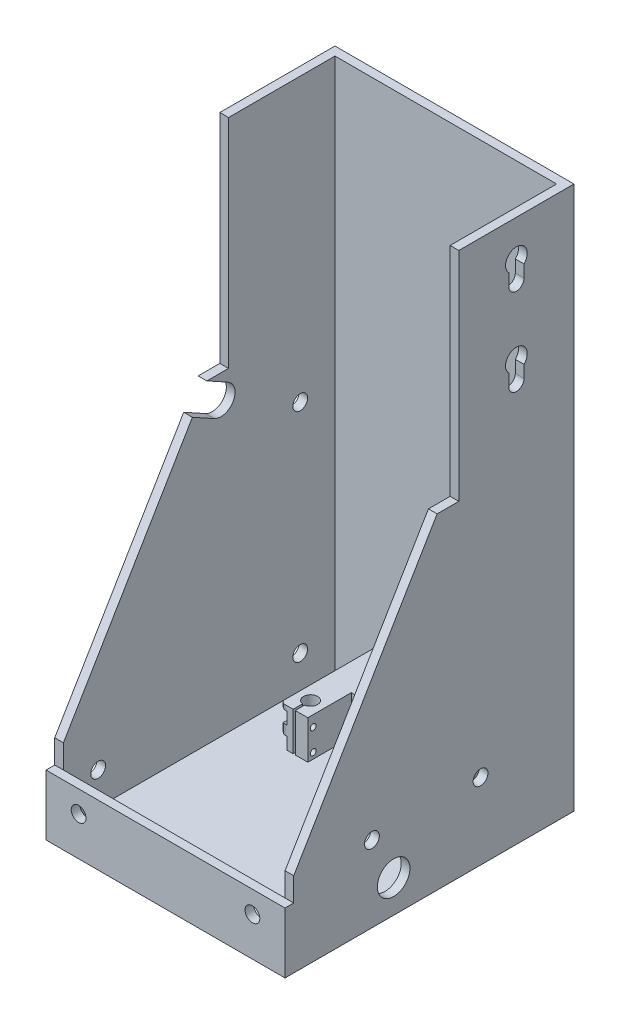
SolidWorks part; units mm, degrees
ref_plane "Front Plane" through (0, 0, 0) normal (0, 0, 1) x (1, 0, 0)
ref_plane "Top Plane" through (0, 0, 0) normal (0, 1, 0) x (1, 0, 0)
ref_plane "Right Plane" through (0, 0, 0) normal (1, 0, 0) x (0, 0, -1)
sketch "Sketch3" plane through (0, 0, 0) normal (0, 1, 0) x (1, 0, 0)
  line L0 (-55, 66.5) -> (55, 66.5)
  line L1 (55, 66.5) -> (55, -66.5)
  line L2 (55, -66.5) -> (-55, -66.5)
  line L3 (-55, -66.5) -> (-55, 66.5)
  point P2 (0, 66.5)
  point P6 (-55, 0)
  dimension "D1" = 133
  dimension "D2" = 110
extrude "Boss-Extrude1" add sketch "Sketch3" along normal blind 5
sketch "Sketch4" plane through (0, 5, 0) normal (0, 1, 0) x (1, 0, 0)
  line L0 (-55, -66.5) -> (-55, 66.5)
  line L1 (-55, 66.5) -> (55, 66.5)
  line L2 (55, 66.5) -> (55, -66.5)
  line L3 (55, -66.5) -> (-55, -66.5)
  line L4 (-51, 62.5) -> (51, 62.5)
  line L5 (51, 62.5) -> (51, -62.5)
  line L6 (51, -62.5) -> (-51, -62.5)
  line L7 (-51, -62.5) -> (-51, 62.5)
  dimension "D1" = 4
  dimension "D2" = 4
  dimension "D3" = 4
  dimension "D4" = 4
extrude "Boss-Extrude2" add sketch "Sketch4" along normal blind 245
sketch "Sketch5" plane through (-55, 0, 0) normal (-1, 0, 0) x (0, 0, 1)
  line L0 (-13.5, 250) -> (-13.5, 150)
  line L1 (-66.5, 250) -> (66.5, 250) construction
  line L2 (-13.5, 150) -> (-3.5, 150)
  line L3 (66.5, 27.9) -> (62.5, 27.9)
  line L4 (66.5, 250) -> (66.5, 0) construction
  line L5 (62.5, 27.9) -> (62.5, 38.76)
  line L6 (-3.5, 150) -> (62.5, 38.76)
  line L7 (-13.5, 250) -> (66.5, 250)
  line L8 (66.5, 250) -> (66.5, 27.9)
  dimension "D1" = 100
  dimension "D2" = 53
  dimension "D3" = 10
  dimension "D4" = 27.9
  dimension "D5" = 4
  dimension "D6" = 10.86
extrude "Cut-Extrude1" cut sketch "Sketch5" against normal through all
sketch "Sketch6" plane through (0, 5, 0) normal (0, 1, 0) x (1, 0, 0)
  line L0 (-31, 62.5) -> (31.5, 62.5)
  line L1 (51, 62.5) -> (-51, 62.5) construction
  line L2 (-31, 62.5) -> (-31, 37.5)
  line L3 (-31, 37.5) -> (31.5, 37.5)
  line L4 (31.5, 37.5) -> (31.5, 62.5)
  dimension "D1" = 20
  dimension "D2" = 19.5
  dimension "D3" = 25
extrude "Boss-Extrude3" add sketch "Sketch6" along normal blind 20
sketch "Sketch7" plane through (0, 25, 0) normal (0, 1, 0) x (1, 0, 0)
  line L0 (31.5, 62.5) -> (-31, 62.5) construction
  line L1 (31.5, 37.5) -> (31.5, 62.5) construction
  circle A0 centre (0.25, 45) radius 2.75
  dimension "D1" = 5.5
  dimension "D2" = 17.5
  dimension "D3" = 31.25
extrude "Cut-Extrude2" cut sketch "Sketch7" against normal blind 20
sketch "Sketch8" plane through (0, 5, 0) normal (0, 1, 0) x (1, 0, 0)
  line L0 (-31, 37.5) -> (-31, 17.5)
  line L1 (-31, 17.5) -> (-18.5, 17.5)
  line L2 (-18.5, 17.5) -> (-18.5, 37.5)
  line L3 (-31, 37.5) -> (31.5, 37.5) construction
  line L4 (-18.5, 37.5) -> (-31, 37.5)
  line L5 (31.5, 37.5) -> (31.5, 17.5)
  line L6 (31.5, 17.5) -> (19, 17.5)
  line L7 (19, 17.5) -> (19, 37.5)
  line L8 (-31, 37.5) -> (31.5, 37.5) construction
  line L9 (19, 37.5) -> (31.5, 37.5)
  dimension "D1" = 20
  dimension "D2" = 20
  dimension "D3" = 12.5
  dimension "D4" = 12.5
extrude "Boss-Extrude4" add sketch "Sketch8" along normal blind 20
sketch "Sketch9" plane through (0, 25, 0) normal (0, 1, 0) x (1, 0, 0)
  line L0 (-18.5, 37.5) -> (19, 37.5) construction
  line L1 (19, 37.5) -> (19, 17.5) construction
  line L2 (-18.5, 17.5) -> (-18.5, 37.5) construction
  circle A0 centre (-24.75, 25) radius 3.25
  circle A1 centre (25.25, 25) radius 3.25
  dimension "D1" = 6.5
  dimension "D2" = 6.5
  dimension "D3" = 12.5
  dimension "D4" = 6.25
  dimension "D5" = 6.25
extrude "Cut-Extrude3" cut sketch "Sketch9" against normal blind 20
sketch "Sketch10" plane through (-18.5, 0, 0) normal (1, 0, 0) x (0, 0, -1)
  line L0 (37.5, 5) -> (37.5, 7.25)
  line L1 (37.5, 25) -> (37.5, 5) construction
  line L2 (37.5, 7.25) -> (17.5, 7.25)
  line L3 (17.5, 25) -> (17.5, 5) construction
  line L4 (17.5, 7.25) -> (17.5, 5)
  line L5 (17.5, 5) -> (37.5, 5)
  dimension "D1" = 2.25
extrude "Cut-Extrude4" cut sketch "Sketch10" against normal blind 12.6
sketch "Sketch12" plane through (19, 0, 0) normal (-1, 0, 0) x (0, 0, 1)
  line L0 (-37.5, 5) -> (-37.5, 7.25)
  line L1 (-37.5, 25) -> (-37.5, 5) construction
  line L2 (-37.5, 7.25) -> (-17.5, 7.25)
  line L3 (-17.5, 25) -> (-17.5, 5) construction
  line L4 (-17.5, 7.25) -> (-17.5, 5)
  line L5 (-17.5, 5) -> (-37.5, 5)
  dimension "D1" = 2.25
extrude "Cut-Extrude5" cut sketch "Sketch12" against normal blind 12.6
fillet "Fillet1" radius 2 1 edges at (31.5, 16.125, -17.5)
fillet "Fillet2" radius 2 1 edges at (-31, 16.125, -17.5)
sketch "Sketch13" plane through (0, 25, 0) normal (0, 1, 0) x (1, 0, 0)
  line L0 (25.75, 17.5) -> (25.75, 22.7898)
  line L1 (19, 17.5) -> (29.5, 17.5) construction
  line L2 (25.75, 22.7898) -> (24.75, 22.7898)
  line L3 (24.75, 22.7898) -> (24.75, 17.5)
  line L4 (24.75, 17.5) -> (25.75, 17.5)
  line L5 (31.5, 19.5) -> (31.5, 62.5) construction
  line L6 (-24.25, 17.5) -> (-25.25, 17.5)
  line L7 (-29, 17.5) -> (-18.5, 17.5) construction
  line L8 (-25.25, 17.5) -> (-25.25, 22.7898)
  line L9 (-25.25, 22.7898) -> (-24.25, 22.7898)
  line L10 (-24.25, 22.7898) -> (-24.25, 17.5)
  line L11 (-31, 62.5) -> (-31, 19.5) construction
  point P6 (25.25, 17.5)
  point P13 (-24.75, 17.5)
  dimension "D1" = 6.25
  dimension "D2" = 1
  dimension "D3" = 5.2898
  dimension "D4" = 6.25
  dimension "D5" = 1
  dimension "D6" = 5.2898
extrude "Cut-Extrude6" cut sketch "Sketch13" against normal blind 20
sketch "Sketch14" plane through (-18.5, 0, 0) normal (1, 0, 0) x (0, 0, -1)
  line L0 (17.5, 25) -> (37.5, 25) construction
  line L1 (17.5, 25) -> (17.5, 7.25) construction
  circle A0 centre (20, 20) radius 1.375
  circle A1 centre (20, 10) radius 1.375
  dimension "D1" = 2.75
  dimension "D2" = 2.75
  dimension "D3" = 10
  dimension "D4" = 5
  dimension "D5" = 2.5
extrude "Cut-Extrude7" cut sketch "Sketch14" against normal blind 20
sketch "Sketch15" plane through (19, 0, 0) normal (-1, 0, 0) x (0, 0, 1)
  line L0 (-37.5, 25) -> (-17.5, 25) construction
  line L1 (-17.5, 25) -> (-17.5, 7.25) construction
  circle A0 centre (-19.75, 20) radius 1.375
  circle A1 centre (-19.75, 10) radius 1.375
  dimension "D1" = 2.75
  dimension "D2" = 2.75
  dimension "D3" = 10
  dimension "D4" = 5
  dimension "D5" = 2.25
extrude "Cut-Extrude8" cut sketch "Sketch15" against normal blind 20
sketch "Sketch16" plane through (-31, 0, 0) normal (-1, 0, 0) x (0, 0, 1)
  line L0 (-62.5, 25) -> (-19.5, 25) construction
  line L1 (-17.5, 7.25) -> (-17.5, 25) construction
  circle A0 centre (-20, 20) radius 3.75
  circle A1 centre (-20, 10) radius 3.75
  dimension "D1" = 7.5
  dimension "D4" = 7.5
  dimension "D2" = 5
  dimension "D3" = 2.5
  dimension "D5" = 10
extrude "Cut-Extrude9" cut sketch "Sketch16" against normal blind 3
sketch "Sketch17" plane through (31.5, 0, 0) normal (1, 0, 0) x (0, 0, -1)
  line L0 (19.5, 25) -> (62.5, 25) construction
  line L1 (17.5, 7.25) -> (17.5, 25) construction
  circle A0 centre (20, 20) radius 3.75
  circle A1 centre (20, 10) radius 3.75
  dimension "D1" = 7.5
  dimension "D2" = 7.5
  dimension "D3" = 5
  dimension "D4" = 10
  dimension "D5" = 2.5
extrude "Cut-Extrude10" cut sketch "Sketch17" against normal blind 3
sketch "Sketch18" plane through (0, 0, 66.5) normal (0, 0, 1) x (1, 0, 0)
  line L0 (-55, 0) -> (55, 0) construction
  line L1 (-55, 27.9) -> (-55, 0) construction
  circle A0 centre (-40, 17.9) radius 3.41
  circle A1 centre (40, 17.9) radius 3.41
  dimension "D1" = 6.82
  dimension "D2" = 6.82
  dimension "D3" = 80
  dimension "D4" = 17.9
  dimension "D5" = 15
extrude "Cut-Extrude11" cut sketch "Sketch18" against normal blind 5
sketch "Sketch19" plane through (-55, 0, 0) normal (-1, 0, 0) x (0, 0, 1)
  line L0 (-13.5, 150) -> (-3.5, 150) construction
  line L2 (-66.5, 250) -> (-66.5, 0) construction
  line L3 (-66.5, 0) -> (66.5, 0) construction
  line L4 (66.5, 27.9) -> (66.5, 0) construction
  circle A0 centre (-46.5, 120) radius 3.41
  circle A1 centre (-46.5, 20) radius 3.41
  circle A2 centre (46.5, 20) radius 3.41
  dimension "D1" = 6.82
  dimension "D2" = 6.82
  dimension "D3" = 6.82
  dimension "D4" = 30
  dimension "D5" = 20
  dimension "D6" = 20
  dimension "D7" = 20
extrude "Cut-Extrude12" cut sketch "Sketch19" against normal blind 5
sketch "Sketch20" plane through (-55, 0, 0) normal (-1, 0, 0) x (0, 0, 1)
  line L0 (-66.5, 250) -> (-66.5, 0) construction
  line L1 (-13.5, 150) -> (-3.5, 150) construction
  line L2 (3.1334, 138.8197) -> (-6.8611, 133.3081)
  line L3 (-3.5, 150) -> (62.5, 38.76) construction
  line L4 (-3.5, 150) -> (-13.1355, 144.6937)
  line L5 (-3.5, 150) -> (3.1334, 138.8197)
  arc A0 (-13.1355, 144.6937) -> (-6.8611, 133.3081) centre (-10, 139) ccw
  dimension "D1" = 13
  dimension "D2" = 56.5
  dimension "D3" = 11
  dimension "D4" = 13
extrude "Cut-Extrude13" cut sketch "Sketch20" against normal blind 5
sketch "Sketch21" plane through (55, 0, 0) normal (1, 0, 0) x (0, 0, -1)
  line L0 (-66.5, 27.9) -> (-66.5, 0) construction
  line L1 (-66.5, 0) -> (66.5, 0) construction
  circle A0 centre (-16.5, 15) radius 7.5
  dimension "D1" = 15
  dimension "D2" = 50
  dimension "D3" = 15
extrude "Cut-Extrude14" cut sketch "Sketch21" against normal blind 5
sketch "Sketch22" plane through (55, 0, 0) normal (1, 0, 0) x (0, 0, -1)
  line L0 (-62.5, 38.76) -> (-62.5, 27.9) construction
  line L1 (-66.5, 0) -> (66.5, 0) construction
  circle A0 centre (-26.5, 35) radius 3.41
  circle A1 centre (23.5, 35) radius 3.41
  dimension "D1" = 6.82
  dimension "D2" = 6.82
  dimension "D3" = 36
  dimension "D4" = 50
  dimension "D5" = 35
extrude "Cut-Extrude15" cut sketch "Sketch22" against normal blind 5
sketch "Sketch23" plane through (55, 0, 0) normal (1, 0, 0) x (0, 0, -1)
  line L0 (66.5, 250) -> (66.5, 0) construction
  line L2 (13.5, 250) -> (66.5, 250) construction
  line L3 (36.5, 224) -> (36.5, 229.6293)
  line L4 (43.5, 224) -> (43.5, 229.6293)
  line L5 (36.5, 184) -> (36.5, 189.6293)
  line L6 (43.5, 184) -> (43.5, 189.6293)
  arc A0 (36.5, 224) -> (43.5, 224) centre (40, 224) ccw
  arc A1 (36.5, 184) -> (43.5, 184) centre (40, 184) ccw
  arc A2 (43.5, 229.6293) -> (36.5, 229.6293) centre (40, 233.2) ccw
  arc A3 (43.5, 189.6293) -> (36.5, 189.6293) centre (40, 193.2) ccw
  dimension "D1" = 7
  dimension "D2" = 7
  dimension "D6" = 10
  dimension "D8" = 10
  dimension "D3" = 26.5
  dimension "D4" = 40
  dimension "D5" = 26
  dimension "D7" = 9.2
  dimension "D9" = 9.2
extrude "Cut-Extrude16" cut sketch "Sketch23" against normal blind 5
